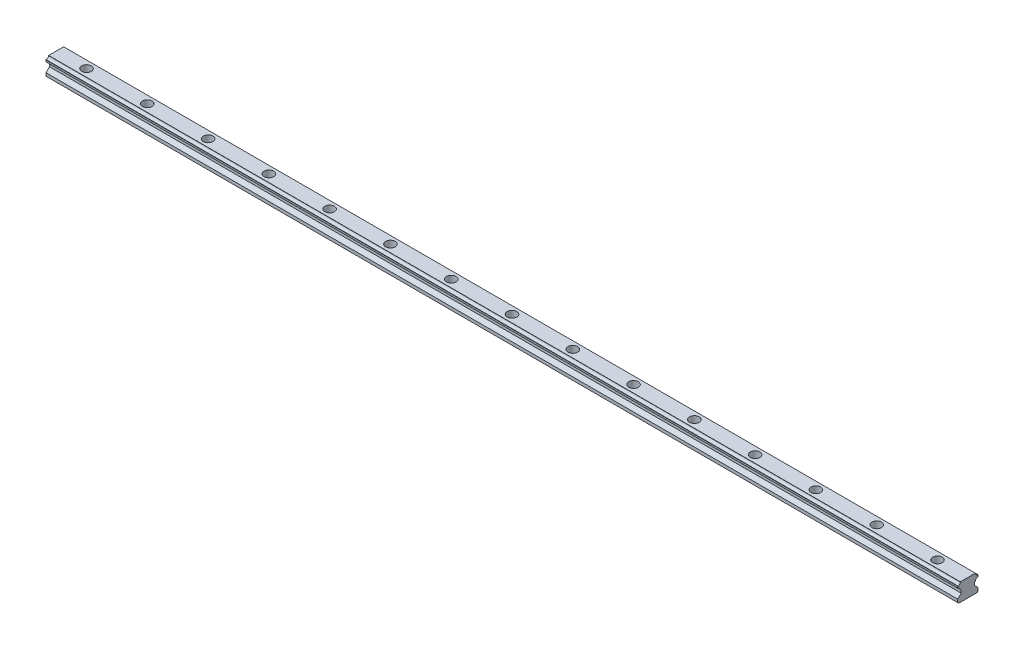
SolidWorks part; units mm, degrees
material "201 Отожженная нержавеющая сталь (SS)"
ref_plane "Спереди" through (0, 0, 0) normal (0, 0, 1) x (1, 0, 0)
ref_plane "Сверху" through (0, 0, 0) normal (0, 1, 0) x (1, 0, 0)
ref_plane "Сбоку" through (0, 0, 0) normal (1, 0, 0) x (0, 0, -1)
sketch "Эскиз1" plane through (0, 0, 0) normal (1, 0, 0) x (0, 0, -1)
  line L0 (-10, 0.9899) -> (-9.0101, 0)
  line L1 (-9.0101, 0) -> (9.0101, 0)
  line L2 (9.0101, 0) -> (10, 0.9899)
  line L3 (10, 0.9899) -> (10, 4)
  line L4 (10, 4) -> (6.6, 7.4)
  line L5 (6.6, 7.4) -> (6.6, 9.9)
  line L6 (6.6, 9.9) -> (7.5, 10.8)
  line L7 (9.8, 13.1) -> (10, 13.3)
  line L8 (10, 13.3) -> (10, 14.9)
  line L9 (10, 14.9) -> (9.8, 15.1)
  line L10 (7.5, 17.4) -> (7.4, 17.5)
  line L11 (7.4, 17.5) -> (-7.4, 17.5)
  line L12 (-7.4, 17.5) -> (-7.5, 17.4)
  line L13 (-9.8, 15.1) -> (-10, 14.9)
  line L14 (-10, 14.9) -> (-10, 13.3)
  line L15 (-10, 13.3) -> (-9.8, 13.1)
  line L16 (-7.5, 10.8) -> (-6.6, 9.9)
  line L17 (-6.6, 9.9) -> (-6.6, 7.4)
  line L18 (-6.6, 7.4) -> (-10, 4)
  line L19 (-10, 4) -> (-10, 0.9899)
  arc A0 (7.5, 10.8) -> (9.8, 13.1) centre (9.8, 10.8) cw
  arc A1 (9.8, 15.1) -> (7.5, 17.4) centre (9.8, 17.4) cw
  arc A2 (-7.5, 17.4) -> (-9.8, 15.1) centre (-9.8, 17.4) cw
  arc A3 (-9.8, 13.1) -> (-7.5, 10.8) centre (-9.8, 10.8) cw
  dimension "D1" = 20
  dimension "D2" = 17.5
extrude "Бобышка-Вытянуть1" add sketch "Эскиз1" against normal mid plane 900
hole_wizard "Цековка M6 для болта с шестигранной головкой класса А ГОСТ 78051" positions "Трехмерный эскиз1" profile "Эскиз4" counterbore size "M6" standard "ГОСТ"
sketch3d "Трехмерный эскиз1"
  line L5 (-450, 17.5, 0) -> (450, 17.5, 0) construction
  line L6 (-450, 17.5, -7.4) -> (-450, 17.5, 7.4) construction
  line L7 (450, 17.5, -7.4) -> (450, 17.5, 7.4) construction
  point P34 (0.3531, 17.5, 0)
  point P49 (0, 17.5, 0)
sketch "Эскиз4" plane through (0, 17.5, 0) normal (1, 0, 0) x (0, 0, 1)
  line L0 (0, 0) -> (0, 19.3016)
  line L1 (0, 19.3016) -> (3, 17.499)
  line L2 (3, 17.499) -> (3, 8.5)
  line L3 (3, 8.5) -> (4.75, 8.5)
  line L4 (4.75, 8.5) -> (4.75, 0)
  line L5 (4.75, 0) -> (0, 0)
  line L10 (0, 19.3016) -> (-3, 17.499) construction
  line L11 (0, -6.35) -> (0, 107.95) construction
  dimension "Диаметр отверстия" = 6
  dimension "Глубина отверстия" = 17.499
  dimension "Диаметр цековки" = 9.5
  dimension "Глубина цековки" = 8.5
  dimension "Угол заточки сверла" = 118
pattern_linear "Линейный массив1" count 8 spacing 60 along (1, 0, 0) of "Цековка M6 для болта с шестигранной головкой класса А ГОСТ 78051"
pattern_linear "Линейный массив2" count 8 spacing 60 along (-1, 0, 0) of "Цековка M6 для болта с шестигранной головкой класса А ГОСТ 78051"
